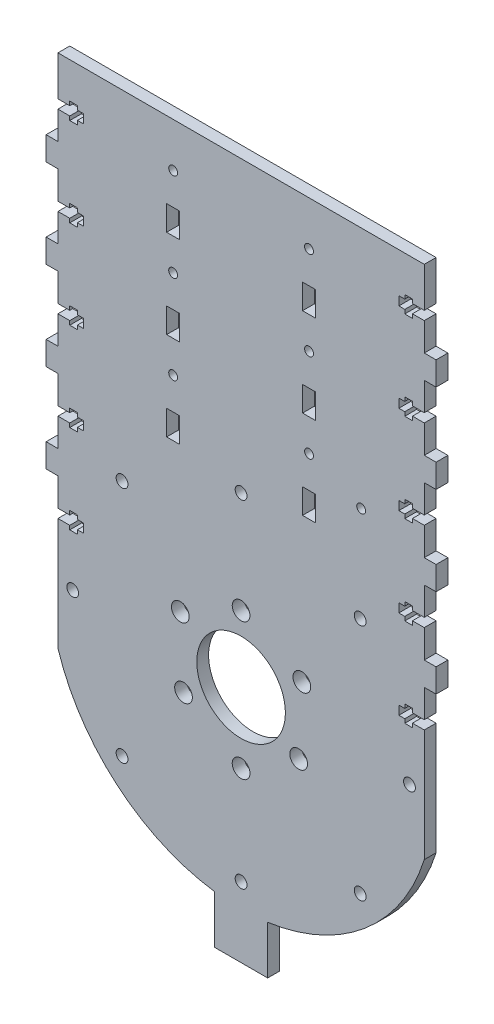
SolidWorks part; units mm, degrees
ref_plane "前视基准面" through (0, 0, 0) normal (0, 0, 1) x (1, 0, 0)
ref_plane "上视基准面" through (0, 0, 0) normal (0, 1, 0) x (1, 0, 0)
ref_plane "右视基准面" through (0, 0, 0) normal (1, 0, 0) x (0, 0, -1)
sketch "草图1" plane through (0, 0, 0) normal (0, 0, 1) x (1, 0, 0)
  line L9 (145, 46.5) -> (149, 46.5)
  line L10 (149, 46.5) -> (149, 45.15)
  line L11 (149, 45.15) -> (151.6, 45.15)
  line L12 (151.6, 45.15) -> (151.6, 46.5)
  line L13 (151.6, 46.5) -> (153.6, 46.5)
  line L14 (153.6, 46.5) -> (153.6, 49.5)
  line L23 (145, 48) -> (143.6922, 48) construction
  line L24 (145, 46.5) -> (145, 49.5) construction
  line L25 (151.6, 50.85) -> (151.6, 49.5)
  line L26 (149, 49.5) -> (149, 50.85)
  line L27 (151.6, 49.5) -> (153.6, 49.5)
  line L28 (149, 50.85) -> (151.6, 50.85)
  line L29 (145, 49.5) -> (149, 49.5)
  line L31 (145, 29) -> (141, 29)
  line L32 (141, 29) -> (141, 37)
  line L33 (141, 37) -> (145, 37)
  line L34 (145, 37) -> (145, 46.5)
  line L35 (141, 33) -> (142.703, 33) construction
  line L43 (149, 15.15) -> (151.6, 15.15)
  line L44 (151.6, 16.5) -> (153.6, 16.5)
  line L45 (149, 16.5) -> (149, 15.15)
  line L69 (145, 123) -> (269, 123)
  line L70 (151.6, 15.15) -> (151.6, 16.5)
  line L71 (153.6, 19.5) -> (153.6, 16.5)
  line L72 (151.6, 19.5) -> (153.6, 19.5)
  line L73 (151.6, 20.85) -> (151.6, 19.5)
  line L98 (149, 20.85) -> (151.6, 20.85)
  line L123 (149, 19.5) -> (149, 20.85)
  line L124 (145, 7) -> (145, 16.5)
  line L125 (149, 16.5) -> (145, 16.5)
  line L126 (149, 19.5) -> (145, 19.5)
  line L127 (145, 19.5) -> (145, 29)
  line L128 (153.6, 18) -> (150.6786, 18) construction
  line L129 (141, 3) -> (142.703, 3) construction
  line L130 (141, -1) -> (145, -1)
  line L131 (141, 7) -> (141, -1)
  line L132 (145, 7) -> (141, 7)
  line L133 (145, -1) -> (145, -10.5)
  line L134 (149, -10.5) -> (145, -10.5)
  line L135 (149, -13.5) -> (145, -13.5)
  line L136 (153.6, -12) -> (150.6786, -12) construction
  line L137 (149, -13.5) -> (149, -14.85)
  line L138 (149, -14.85) -> (151.6, -14.85)
  line L139 (151.6, -14.85) -> (151.6, -13.5)
  line L140 (151.6, -13.5) -> (153.6, -13.5)
  line L141 (153.6, -13.5) -> (153.6, -10.5)
  line L142 (151.6, -9.15) -> (151.6, -10.5)
  line L143 (149, -10.5) -> (149, -9.15)
  line L144 (151.6, -10.5) -> (153.6, -10.5)
  line L145 (149, -9.15) -> (151.6, -9.15)
  line L146 (153.6, 108) -> (150.6786, 108) construction
  line L147 (141, 93) -> (142.703, 93) construction
  line L148 (153.6, 78) -> (150.6786, 78) construction
  line L149 (141, 63) -> (142.703, 63) construction
  line L150 (145, 46.5) -> (149, 46.5)
  line L151 (149, 46.5) -> (149, 45.15)
  line L152 (149, 45.15) -> (151.6, 45.15)
  line L153 (151.6, 45.15) -> (151.6, 46.5)
  line L154 (151.6, 46.5) -> (153.6, 46.5)
  line L155 (151.6, 50.85) -> (151.6, 49.5)
  line L156 (149, 49.5) -> (149, 50.85)
  line L157 (151.6, 49.5) -> (153.6, 49.5)
  line L158 (145, 46.5) -> (149, 46.5)
  line L159 (149, 45.15) -> (151.6, 45.15)
  line L160 (151.6, 46.5) -> (153.6, 46.5)
  line L161 (149, 46.5) -> (149, 45.15)
  line L162 (151.6, 45.15) -> (151.6, 46.5)
  line L163 (151.6, 49.5) -> (153.6, 49.5)
  line L164 (151.6, 50.85) -> (151.6, 49.5)
  line L165 (149, 50.85) -> (151.6, 50.85)
  line L166 (149, 49.5) -> (149, 50.85)
  line L167 (145, 49.5) -> (149, 49.5)
  line L168 (149, 50.85) -> (151.6, 50.85)
  line L169 (145, 49.5) -> (149, 49.5)
  line L170 (149, 105.15) -> (151.6, 105.15)
  line L171 (151.6, 106.5) -> (153.6, 106.5)
  line L172 (149, 106.5) -> (149, 105.15)
  line L173 (151.6, 105.15) -> (151.6, 106.5)
  line L174 (153.6, 109.5) -> (153.6, 106.5)
  line L175 (151.6, 109.5) -> (153.6, 109.5)
  line L177 (151.6, 110.85) -> (151.6, 109.5)
  line L178 (149, 110.85) -> (151.6, 110.85)
  line L179 (149, 109.5) -> (149, 110.85)
  line L180 (149, 109.5) -> (145, 109.5)
  line L181 (149, 106.5) -> (145, 106.5)
  line L182 (145, 97) -> (145, 106.5)
  line L183 (145, 89) -> (141, 89)
  line L184 (141, 89) -> (141, 97)
  line L185 (141, 97) -> (145, 97)
  line L186 (145, 76.5) -> (145, 67)
  line L187 (149, 76.5) -> (145, 76.5)
  line L188 (149, 79.5) -> (145, 79.5)
  line L189 (145, 89) -> (145, 79.5)
  line L190 (149, 76.5) -> (149, 75.15)
  line L191 (149, 75.15) -> (151.6, 75.15)
  line L192 (151.6, 75.15) -> (151.6, 76.5)
  line L193 (151.6, 76.5) -> (153.6, 76.5)
  line L194 (153.6, 76.5) -> (153.6, 79.5)
  line L195 (151.6, 80.85) -> (151.6, 79.5)
  line L196 (149, 79.5) -> (149, 80.85)
  line L197 (151.6, 79.5) -> (153.6, 79.5)
  line L198 (149, 80.85) -> (151.6, 80.85)
  line L199 (145, 59) -> (145, 49.5)
  line L200 (141, 59) -> (145, 59)
  line L201 (141, 67) -> (141, 59)
  line L202 (145, 67) -> (141, 67)
  line L203 (145, 46.5) -> (149, 46.5)
  line L204 (149, 45.15) -> (151.6, 45.15)
  line L205 (151.6, 46.5) -> (153.6, 46.5)
  line L206 (149, 46.5) -> (149, 45.15)
  line L207 (151.6, 45.15) -> (151.6, 46.5)
  line L208 (151.6, 49.5) -> (153.6, 49.5)
  line L209 (151.6, 50.85) -> (151.6, 49.5)
  line L210 (149, 50.85) -> (151.6, 50.85)
  line L211 (149, 49.5) -> (149, 50.85)
  line L212 (145, 49.5) -> (149, 49.5)
  line L213 (273, 63) -> (271.297, 63) construction
  line L214 (260.4, 78) -> (263.3214, 78) construction
  line L215 (273, 93) -> (271.297, 93) construction
  line L216 (260.4, 108) -> (263.3214, 108) construction
  line L217 (260.4, -12) -> (263.3214, -12) construction
  line L218 (273, 3) -> (271.297, 3) construction
  line L219 (260.4, 18) -> (263.3214, 18) construction
  line L220 (273, 33) -> (271.297, 33) construction
  line L221 (269, 46.5) -> (269, 49.5) construction
  line L222 (269, 48) -> (270.3078, 48) construction
  line L223 (269, -27) -> (269, -13.5)
  line L224 (269, 123) -> (269, 109.5)
  line L225 (269, -27) -> (269, -97)
  line L227 (269, 49.5) -> (265, 49.5)
  line L228 (265, 49.5) -> (265, 50.85)
  line L229 (265, 50.85) -> (262.4, 50.85)
  line L230 (262.4, 50.85) -> (262.4, 49.5)
  line L231 (262.4, 49.5) -> (260.4, 49.5)
  line L232 (262.4, 45.15) -> (262.4, 46.5)
  line L233 (265, 46.5) -> (265, 45.15)
  line L234 (262.4, 46.5) -> (260.4, 46.5)
  line L235 (265, 45.15) -> (262.4, 45.15)
  line L253 (269, 46.5) -> (265, 46.5)
  line L254 (269, 67) -> (273, 67)
  line L255 (145, -27) -> (145, -97)
  line L256 (269, -97) -> (145, -97)
  line L258 (273, 67) -> (273, 59)
  line L259 (273, 59) -> (269, 59)
  line L260 (269, 59) -> (269, 49.5)
  line L261 (265, 80.85) -> (262.4, 80.85)
  line L262 (262.4, 79.5) -> (260.4, 79.5)
  line L263 (265, 79.5) -> (265, 80.85)
  line L264 (262.4, 80.85) -> (262.4, 79.5)
  line L265 (260.4, 76.5) -> (260.4, 79.5)
  line L267 (262.4, 76.5) -> (260.4, 76.5)
  line L269 (262.4, 75.15) -> (262.4, 76.5)
  line L270 (265, 75.15) -> (262.4, 75.15)
  line L272 (265, 76.5) -> (265, 75.15)
  line L273 (269, 89) -> (269, 79.5)
  line L274 (265, 79.5) -> (269, 79.5)
  line L275 (265, 76.5) -> (269, 76.5)
  line L277 (269, 76.5) -> (269, 67)
  line L278 (273, 97) -> (269, 97)
  line L279 (273, 89) -> (273, 97)
  line L280 (269, 89) -> (273, 89)
  line L281 (269, 97) -> (269, 106.5)
  line L282 (265, 106.5) -> (269, 106.5)
  line L283 (265, 109.5) -> (269, 109.5)
  line L284 (265, 109.5) -> (265, 110.85)
  line L285 (265, 110.85) -> (262.4, 110.85)
  line L286 (262.4, 110.85) -> (262.4, 109.5)
  line L287 (262.4, 109.5) -> (260.4, 109.5)
  line L288 (260.4, 109.5) -> (260.4, 106.5)
  line L289 (262.4, 105.15) -> (262.4, 106.5)
  line L290 (265, 106.5) -> (265, 105.15)
  line L291 (262.4, 106.5) -> (260.4, 106.5)
  line L292 (265, 105.15) -> (262.4, 105.15)
  line L293 (269, 49.5) -> (265, 49.5)
  line L294 (265, 50.85) -> (262.4, 50.85)
  line L295 (269, 49.5) -> (265, 49.5)
  line L296 (265, 49.5) -> (265, 50.85)
  line L298 (265, 50.85) -> (262.4, 50.85)
  line L299 (262.4, 50.85) -> (262.4, 49.5)
  line L300 (262.4, 49.5) -> (260.4, 49.5)
  line L301 (262.4, 45.15) -> (262.4, 46.5)
  line L302 (265, 46.5) -> (265, 45.15)
  line L303 (262.4, 46.5) -> (260.4, 46.5)
  line L304 (265, 45.15) -> (262.4, 45.15)
  line L305 (269, 46.5) -> (265, 46.5)
  line L306 (262.4, 49.5) -> (260.4, 49.5)
  line L307 (265, 49.5) -> (265, 50.85)
  line L308 (262.4, 50.85) -> (262.4, 49.5)
  line L309 (262.4, 46.5) -> (260.4, 46.5)
  line L310 (262.4, 45.15) -> (262.4, 46.5)
  line L312 (265, 45.15) -> (262.4, 45.15)
  line L314 (265, 46.5) -> (265, 45.15)
  line L315 (269, 46.5) -> (265, 46.5)
  line L317 (265, -9.15) -> (262.4, -9.15)
  line L320 (262.4, -10.5) -> (260.4, -10.5)
  line L321 (265, -10.5) -> (265, -9.15)
  line L322 (262.4, -9.15) -> (262.4, -10.5)
  line L323 (260.4, -13.5) -> (260.4, -10.5)
  line L324 (262.4, -13.5) -> (260.4, -13.5)
  line L325 (262.4, -14.85) -> (262.4, -13.5)
  line L326 (265, -14.85) -> (262.4, -14.85)
  line L327 (265, -13.5) -> (265, -14.85)
  line L328 (265, -13.5) -> (269, -13.5)
  line L329 (265, -10.5) -> (269, -10.5)
  line L330 (269, -1) -> (269, -10.5)
  line L331 (269, 7) -> (273, 7)
  line L332 (273, 7) -> (273, -1)
  line L333 (273, -1) -> (269, -1)
  line L334 (269, 19.5) -> (269, 29)
  line L335 (265, 19.5) -> (269, 19.5)
  line L336 (265, 16.5) -> (269, 16.5)
  line L337 (269, 7) -> (269, 16.5)
  line L338 (265, 19.5) -> (265, 20.85)
  line L339 (265, 20.85) -> (262.4, 20.85)
  line L340 (262.4, 20.85) -> (262.4, 19.5)
  line L341 (262.4, 19.5) -> (260.4, 19.5)
  line L342 (260.4, 19.5) -> (260.4, 16.5)
  line L343 (262.4, 15.15) -> (262.4, 16.5)
  line L344 (265, 16.5) -> (265, 15.15)
  line L345 (262.4, 16.5) -> (260.4, 16.5)
  line L346 (265, 15.15) -> (262.4, 15.15)
  line L347 (269, 37) -> (269, 46.5)
  line L348 (273, 37) -> (269, 37)
  line L349 (273, 29) -> (273, 37)
  line L350 (269, 29) -> (273, 29)
  line L351 (269, 49.5) -> (265, 49.5)
  line L352 (265, 50.85) -> (262.4, 50.85)
  line L353 (262.4, 49.5) -> (260.4, 49.5)
  line L354 (265, 49.5) -> (265, 50.85)
  line L355 (262.4, 50.85) -> (262.4, 49.5)
  line L356 (260.4, 46.5) -> (260.4, 49.5)
  line L357 (262.4, 46.5) -> (260.4, 46.5)
  line L358 (262.4, 45.15) -> (262.4, 46.5)
  line L359 (265, 45.15) -> (262.4, 45.15)
  line L360 (265, 46.5) -> (265, 45.15)
  line L361 (269, 46.5) -> (265, 46.5)
  line L592 (145, 123) -> (145, 109.5)
  line L594 (145, -27) -> (145, -13.5)
  circle A87 centre (262.4, -88.9111) radius 2.2834
  point P15 (144.3461, 48)
  dimension "D3" = 4
  dimension "D4" = 2
  dimension "D5" = 2.6
  dimension "D6" = 1.35
  dimension "D8" = 1.5
extrude "凸台-拉伸1" add sketch "草图1" along normal blind 4 contours L594 L255 L256 L225 L223 L328 L327 L326 L325 L324 L323 L320 L322 L317 L321 L329 L330 L333 L332 L331 L337 L336 L344 L346 L343 L345 L342 L341 L340 L339 L338 L335 L334 L350 L349 L348 L347 L253 L233 L235 L232 L234 L356 L231 L230 L229 L228 L227 L260 L259 L258
sketch "草图2" plane through (269, 0, 0) normal (1, 0, 0) x (0, 0, -1)
  line L0 (-2, -10.5) -> (-2, -13.5)
  line L1 (-4, -10.5) -> (0, -10.5) construction
  line L2 (-4, -13.5) -> (0, -13.5) construction
  circle A0 centre (-2, -12) radius 1.5
sketch "草图3" plane through (0, 0, 4) normal (0, 0, 1) x (1, 0, 0)
  line L0 (225, -32) -> (225, -72) construction
  line L1 (225, -72) -> (205, -72) construction
  line L2 (207, -32) -> (246.1973, -32) construction
  line L3 (207, -32) -> (248.5224, -55.973) construction
  line L4 (153.6, 48) -> (260.4, 48) construction
  line L5 (153.6, 46.5) -> (153.6, 49.5) construction
  line L6 (260.4, 46.5) -> (260.4, 49.5) construction
  line L7 (207, 48) -> (207, -32) construction
  circle A0 centre (207, -32) radius 23.75 construction
  circle A1 centre (207, -32) radius 22.5 construction
  circle A2 centre (207, -55.75) radius 3
  circle A5 centre (226.4856, -43.25) radius 3
  circle A8 centre (207, -32) radius 15
  circle A9 centre (264, -32) radius 2
  circle A42 centre (186.4319, -20.125) radius 3
  circle A43 centre (227.5681, -20.125) radius 3
  circle A44 centre (187.5144, -43.25) radius 3
  circle A45 centre (207, -9.5) radius 3
  circle A46 centre (247.3051, -72.3051) radius 2
  circle A47 centre (207, -89) radius 2
  circle A48 centre (166.6949, -72.3051) radius 2
  circle A49 centre (150, -32) radius 2
  circle A50 centre (166.6949, 8.3051) radius 2
  circle A51 centre (207, 25) radius 2
  circle A52 centre (247.3051, 8.3051) radius 2
  dimension "D1" = 47.5
  dimension "D2" = 45
  dimension "D3" = 6
  dimension "D5" = 6
  dimension "D10" = 4
  dimension "D4" = 30
  dimension "D6" = 57
  dimension "D7" = 8
  dimension "D8" = 3
  dimension "D9" = 3
extrude "切除-拉伸1" cut sketch "草图3" against normal blind 4
sketch "草图6" plane through (0, 0, 4) normal (0, 0, 1) x (1, 0, 0)
  line L0 (145, 97) -> (145, 106.5) construction
  line L1 (181.8, 97.2) -> (186.2, 97.2)
  line L2 (181.8, 97.2) -> (181.8, 88.8)
  line L3 (181.8, 88.8) -> (186.2, 88.8)
  line L4 (186.2, 97.2) -> (186.2, 88.8)
  line L5 (181.8, 97.2) -> (186.2, 88.8) construction
  line L6 (181.8, 88.8) -> (186.2, 97.2) construction
  line L7 (181.8, 67.2) -> (186.2, 67.2)
  line L8 (181.8, 67.2) -> (181.8, 58.8)
  line L9 (181.8, 58.8) -> (186.2, 58.8)
  line L10 (186.2, 67.2) -> (186.2, 58.8)
  line L11 (181.8, 37.2) -> (186.2, 37.2)
  line L12 (181.8, 37.2) -> (181.8, 28.8)
  line L13 (181.8, 28.8) -> (186.2, 28.8)
  line L14 (186.2, 37.2) -> (186.2, 28.8)
  line L15 (232.2, 88.8) -> (227.8, 97.2) construction
  line L16 (232.2, 97.2) -> (227.8, 88.8) construction
  line L17 (227.8, 37.2) -> (227.8, 28.8)
  line L18 (232.2, 28.8) -> (227.8, 28.8)
  line L31 (207, 25) -> (207, -9.5) construction
  line L32 (232.2, 37.2) -> (232.2, 28.8)
  line L33 (232.2, 37.2) -> (227.8, 37.2)
  line L34 (227.8, 67.2) -> (227.8, 58.8)
  line L35 (232.2, 58.8) -> (227.8, 58.8)
  line L36 (232.2, 67.2) -> (232.2, 58.8)
  line L37 (232.2, 67.2) -> (227.8, 67.2)
  line L38 (227.8, 97.2) -> (227.8, 88.8)
  line L39 (232.2, 88.8) -> (227.8, 88.8)
  line L40 (232.2, 97.2) -> (232.2, 88.8)
  line L41 (232.2, 97.2) -> (227.8, 97.2)
  circle A0 centre (184, 108) radius 1.5
  circle A1 centre (184, 78) radius 1.5
  circle A2 centre (184, 48) radius 1.5
  circle A4 centre (184, 18) radius 1.5 [skipped]
  circle A8 centre (230, 48) radius 1.5
  circle A9 centre (230, 78) radius 1.5
  circle A10 centre (230, 108) radius 1.5
  point P0 (184, 93)
  point P43 (230, 93)
  point P44 (207, -9.5)
  dimension "D6" = 15
  dimension "D1" = 39
  dimension "D2" = 4.4
  dimension "D3" = 8.4
  dimension "D4" = 4
  dimension "D5" = 3
  dimension "D7" = 4
extrude "切除-拉伸3" cut sketch "草图6" against normal blind 4
sketch "草图7" plane through (0, 0, 4) normal (0, 0, 1) x (1, 0, 0)
  line L0 (142, -32) -> (85.3113, -32)
  line L1 (272, -32) -> (328.6887, -32)
  circle A0 centre (207, -32) radius 65 construction
  circle A1 centre (207, -32) radius 121.6887 construction
  arc A2 (142, -32) -> (272, -32) centre (207, -32) ccw
  arc A3 (85.3113, -32) -> (328.6887, -32) centre (207, -32) ccw
  circle A4 centre (247.6444, 40.7353) radius 1.5
extrude "切除-拉伸5" cut sketch "草图7" against normal blind 10
sketch "草图8" plane through (0, 0, 4) normal (0, 0, 1) x (1, 0, 0)
  line L0 (198, -112.7155) -> (207, -112.7155)
  line L1 (207, -112.7155) -> (216, -112.7155)
  line L2 (216, -112.7155) -> (216, -91)
  line L3 (216, -91) -> (198, -91)
  line L4 (198, -91) -> (198, -112.7155)
extrude "凸台-拉伸2" add sketch "草图8" against normal blind 4
